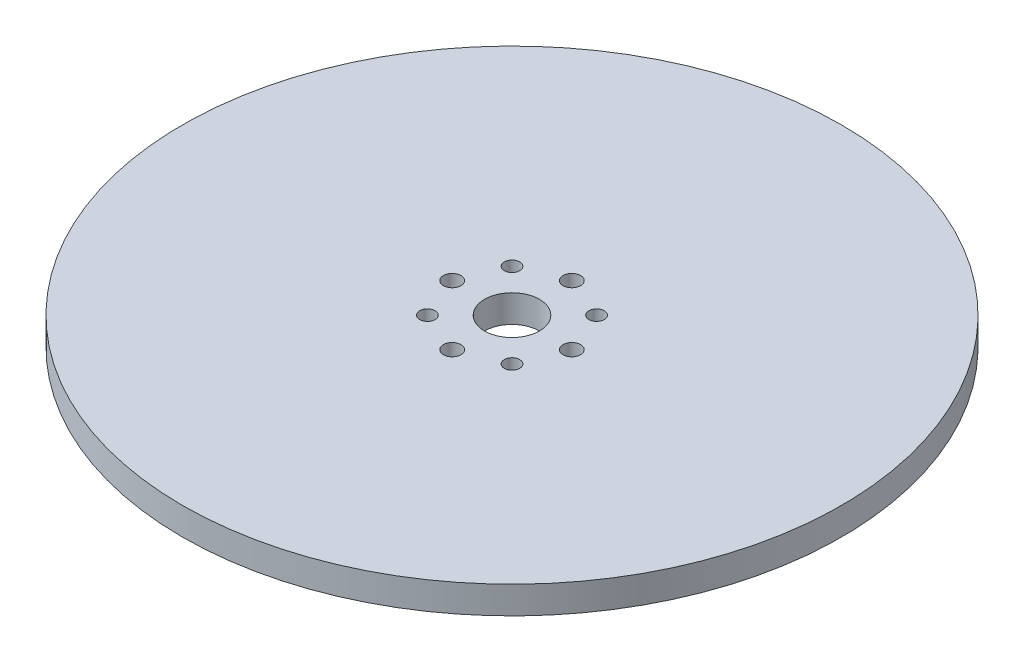
SolidWorks part; units mm, degrees
ref_plane "Front Plane" through (0, 0, 0) normal (0, 0, 1) x (1, 0, 0)
ref_plane "Top Plane" through (0, 0, 0) normal (0, 1, 0) x (1, 0, 0)
ref_plane "Right Plane" through (0, 0, 0) normal (1, 0, 0) x (0, 0, -1)
sketch "Sketch1" plane through (0, 0, 0) normal (0, 1, 0) x (1, 0, 0)
  line L0 (-13.8296, 0) -> (0, -13.8296) construction
  line L1 (-9.779, -9.779) -> (9.779, -9.779) construction
  line L2 (-9.779, -9.779) -> (-9.779, 9.779) construction
  line L3 (-9.779, 9.779) -> (9.779, 9.779) construction
  line L4 (9.779, -9.779) -> (9.779, 9.779) construction
  line L5 (-9.779, -9.779) -> (9.779, 9.779) construction
  line L6 (-9.779, 9.779) -> (9.779, -9.779) construction
  line L7 (-13.8296, 0) -> (0, 13.8296) construction
  line L8 (0, 13.8296) -> (13.8296, 0) construction
  line L9 (0, -13.8296) -> (13.8296, 0) construction
  line L10 (-13.8296, 0) -> (13.8296, 0) construction
  line L11 (0, 13.8296) -> (0, -13.8296) construction
  circle A0 centre (0, 0) radius 76.2
  circle A1 centre (0, 0) radius 6.35
  circle A2 centre (0, 13.8296) radius 2.032
  circle A3 centre (13.8296, 0) radius 2.032
  circle A4 centre (0, -13.8296) radius 2.032
  circle A5 centre (-13.8296, 0) radius 2.032
  circle A6 centre (-9.779, 9.779) radius 1.778
  circle A7 centre (9.779, 9.779) radius 1.778
  circle A8 centre (9.779, -9.779) radius 1.778
  circle A9 centre (-9.779, -9.779) radius 1.778
  point P14 (0, 0)
  point P23 (0, 0)
  point P30 (0, 0)
  dimension "D1" = 2
  dimension "D2" = 4
  dimension "D3" = 4
extrude "Boss-Extrude1" add sketch "Sketch1" along normal blind 6.35
